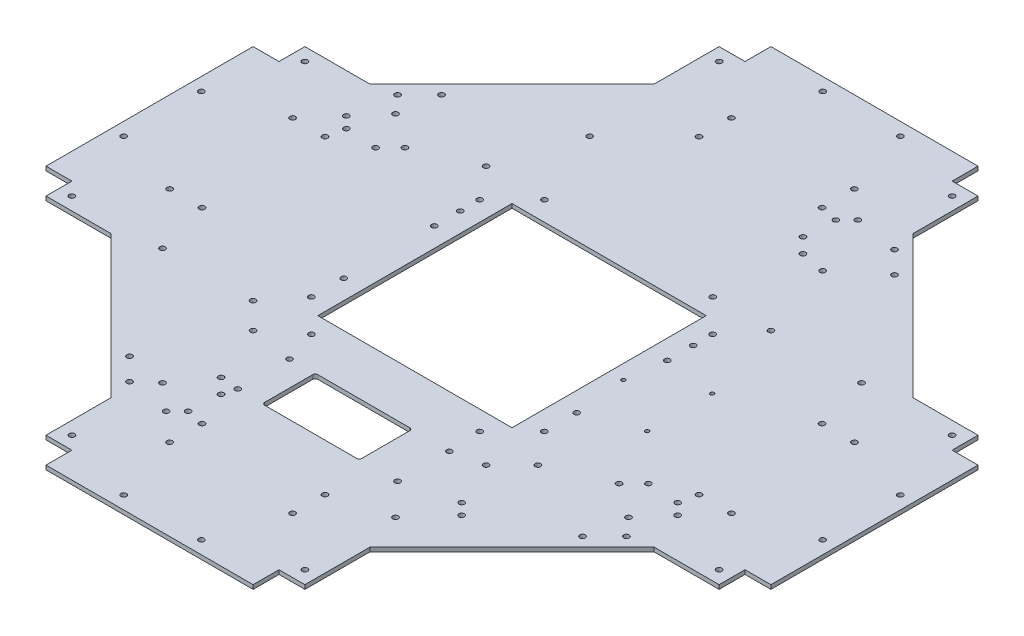
SolidWorks part; units mm, degrees
ref_plane "Front Plane" through (0, 0, 0) normal (0, 0, 1) x (1, 0, 0)
ref_plane "Top Plane" through (0, 0, 0) normal (0, 1, 0) x (1, 0, 0)
ref_plane "Right Plane" through (0, 0, 0) normal (1, 0, 0) x (0, 0, -1)
sketch "Sketch1" plane through (0, 0, 0) normal (0, 1, 0) x (1, 0, 0)
  line L0 (0, -280) -> (100, -280)
  line L1 (100, -280) -> (100, -209.6016)
  line L2 (280, -100) -> (209.6016, -100)
  line L3 (0, 0) -> (0, -280) construction
  line L4 (280, 0) -> (280, -100)
  line L5 (-280, 280) -> (280, 280) construction
  line L6 (-280, 280) -> (-280, -280) construction
  line L7 (-280, -280) -> (280, -280) construction
  line L8 (280, 280) -> (280, -280) construction
  line L9 (-280, 280) -> (280, -280) construction
  line L10 (-280, -280) -> (280, 280) construction
  line L11 (100, -209.6016) -> (209.6016, -100)
  line L12 (-280, 0) -> (-280, -100)
  line L13 (-280, -100) -> (-209.6016, -100)
  line L14 (-209.6016, -100) -> (-100, -209.6016)
  line L15 (-100, -280) -> (-100, -209.6016)
  line L16 (0, -280) -> (-100, -280)
  line L17 (0, 280) -> (-100, 280)
  line L18 (-100, 280) -> (-100, 209.6016)
  line L19 (-100, 209.6016) -> (-209.6016, 100)
  line L20 (-280, 100) -> (-209.6016, 100)
  line L21 (-280, 0) -> (-280, 100)
  line L22 (280, 0) -> (280, 100)
  line L23 (280, 100) -> (209.6016, 100)
  line L24 (209.6016, 100) -> (100, 209.6016)
  line L25 (100, 280) -> (100, 209.6016)
  line L26 (0, 280) -> (100, 280)
  line L27 (111.5258, -219.2889) -> (219.2889, -111.5258) construction
  line L28 (219.2889, -111.5258) -> (247.5732, -139.8101) construction
  line L29 (247.5732, -139.8101) -> (139.8101, -247.5732) construction
  line L30 (139.8101, -247.5732) -> (111.5258, -219.2889) construction
  line L31 (-100, -270) -> (100, -270) construction
  line L32 (-90, -280) -> (-90, 280) construction
  line L37 (-70, -70) -> (70, 70) construction
  line L38 (-70, 70) -> (70, -70) construction
  line L39 (-100, -260) -> (100, -260) construction
  line L40 (-280, 40) -> (280, 40) construction
  line L41 (0, 280) -> (0, 0) construction
  line L42 (-280, -90) -> (280, -90) construction
  line L43 (-260, -100) -> (-260, 100) construction
  line L44 (0, 0) -> (-280, 0) construction
  arc A0 (100, -280) -> (280, -100) centre (100, -100) ccw construction
  circle A1 centre (-47.5, -192) radius 2.125
  circle A2 centre (-47.5, -217) radius 2.125
  circle A3 centre (47.5, -217) radius 2.125
  circle A4 centre (47.5, -192) radius 2.125
  circle A5 centre (-192, 47.5) radius 2.125
  circle A6 centre (-217, 47.5) radius 2.125
  circle A7 centre (-192, -47.5) radius 2.125
  circle A8 centre (-217, -47.5) radius 2.125
  circle A9 centre (47.5, 192) radius 2.125
  circle A10 centre (47.5, 217) radius 2.125
  circle A11 centre (-47.5, 192) radius 2.125
  circle A12 centre (-47.5, 217) radius 2.125
  circle A13 centre (192, -47.5) radius 2.125
  circle A14 centre (217, -47.5) radius 2.125
  circle A15 centre (192, 47.5) radius 2.125
  circle A16 centre (217, 47.5) radius 2.125
  circle A17 centre (-90, -270) radius 2.125
  circle A18 centre (-30, -270) radius 2.125
  circle A19 centre (30, -270) radius 2.125
  circle A20 centre (90, -270) radius 2.125
  circle A21 centre (-270, 90) radius 2.125
  circle A22 centre (-270, 30) radius 2.125
  circle A23 centre (-270, -30) radius 2.125
  circle A24 centre (-270, -90) radius 2.125
  circle A25 centre (90, 270) radius 2.125
  circle A26 centre (30, 270) radius 2.125
  circle A27 centre (-30, 270) radius 2.125
  circle A28 centre (-90, 270) radius 2.125
  circle A29 centre (270, -90) radius 2.125
  circle A30 centre (270, -30) radius 2.125
  circle A31 centre (270, 30) radius 2.125
  circle A32 centre (270, 90) radius 2.125
  circle A33 centre (-90, -250) radius 2.125
  circle A34 centre (-90, -180) radius 2.125
  circle A35 centre (-90, -110) radius 2.125
  circle A36 centre (-90, -40) radius 2.125
  circle A37 centre (-90, 30) radius 2.125
  circle A38 centre (-90, 50) radius 2.125
  circle A39 centre (-90, 100) radius 2.125 construction
  circle A40 centre (-90, 150) radius 2.125
  circle A41 centre (-90, 200) radius 2.125 construction
  circle A42 centre (-90, 250) radius 2.125
  circle A43 centre (90, -250) radius 2.125
  circle A44 centre (90, -180) radius 2.125
  circle A45 centre (90, -110) radius 2.125
  circle A46 centre (90, -40) radius 2.125
  circle A47 centre (90, 30) radius 2.125
  circle A48 centre (90, 50) radius 2.125
  circle A49 centre (90, 100) radius 2.125 construction
  circle A50 centre (90, 150) radius 2.125
  circle A51 centre (90, 200) radius 2.125 construction
  circle A52 centre (90, 250) radius 2.125
  circle A53 centre (-250, -90) radius 2.125
  circle A54 centre (-180, -90) radius 2.125
  circle A55 centre (-110, -90) radius 2.125
  circle A56 centre (-110, 90) radius 2.125
  circle A57 centre (-180, 90) radius 2.125
  circle A58 centre (-250, 90) radius 2.125
  circle A59 centre (110, -90) radius 2.125
  circle A60 centre (180, -90) radius 2.125
  circle A61 centre (250, -90) radius 2.125
  circle A62 centre (110, 90) radius 2.125
  circle A63 centre (180, 90) radius 2.125
  circle A64 centre (250, 90) radius 2.125
  point P33 (0, 0)
  point P68 (0, 0)
  point P107 (0, 0)
  dimension "D10" = 25
  dimension "4.25" = 4.25
  dimension "D11" = 4.25
  dimension "D16" = 4.25
  dimension "D24" = 4.25
  dimension "D28" = 4.25
  dimension "D32" = 4.25
  dimension "D1" = 560
  dimension "D2" = 90
  dimension "D3" = 280
  dimension "D4" = 4
  dimension "D5" = 100
  dimension "D6" = 155
  dimension "D7" = 152.4
  dimension "D8" = 15
  dimension "D9" = 40
  dimension "D12" = 47.5
  dimension "D13" = 63
  dimension "D15" = 10
  dimension "D17" = 10
  dimension "D18" = 76.2
  dimension "D23" = 10
  dimension "D25" = 10
  dimension "D26" = 300
  dimension "D29" = 10
  dimension "D31" = 20
  dimension "D33" = 10
  dimension "D21" = 4
  dimension "D27" = 5
  dimension "D30" = 5
  dimension "D34" = 3
  dimension "D14" = 4
  dimension "D22" = 4
extrude "Boss-Extrude1" add sketch "Sketch1" along normal blind 3.175 contours L26 L17 L18 L19 L20 L21 L12 L13 L14 L15 L16 L0 L1 L11 L2 L4 L22 L23 L24 L25
sketch "Sketch2" plane through (0, 3.175, 0) normal (0, 1, 0) x (1, 0, 0)
  line L0 (-90, -280) -> (-90, 280) construction
  line L1 (-75, -75) -> (75, -75)
  line L2 (-75, -75) -> (-75, 75)
  line L3 (-75, 75) -> (75, 75)
  line L4 (75, -75) -> (75, 75)
  line L5 (-75, -75) -> (75, 75) construction
  line L6 (-75, 75) -> (75, -75) construction
  line L7 (-90, -280) -> (-90, 280) construction
  line L8 (-75, 0) -> (75, 0) construction
  line L9 (0, 75) -> (0, -75) construction
  line L10 (-110, 90) -> (110, 90) construction
  line L11 (37.5, -135) -> (-37.5, -135) construction
  line L16 (-37.5, -155.5) -> (37.5, -155.5)
  line L17 (-37.5, -155.5) -> (-37.5, -114.5)
  line L18 (-37.5, -114.5) -> (37.5, -114.5)
  line L19 (37.5, -155.5) -> (37.5, -114.5)
  line L20 (-37.5, -155.5) -> (37.5, -114.5) construction
  line L21 (-37.5, -114.5) -> (37.5, -155.5) construction
  line L22 (128.2843, -167.1751) -> (98.0356, -136.9265) construction
  line L23 (146.0396, -78.7091) -> (184.862, -39.8867) construction
  line L24 (92.9289, -202.5305) -> (202.5305, -92.9289)
  line L25 (92.9289, -202.5305) -> (202.5305, -92.9289) construction
  line L26 (170.0036, -125.4558) -> (137.8448, -93.2971) construction
  circle A0 centre (66.6, -115) radius 2.125
  circle A1 centre (-90, 65) radius 2.125
  circle A2 centre (-90, -65) radius 2.125
  circle A3 centre (90, -65) radius 2.125
  circle A4 centre (90, 65) radius 2.125
  circle A5 centre (-65, 90) radius 2.125
  circle A6 centre (65, 90) radius 2.125
  circle A7 centre (65, -90) radius 2.125
  circle A8 centre (-65, -90) radius 2.125
  circle A9 centre (66.6, -155) radius 2.125
  circle A10 centre (-56.9, -115) radius 2.1
  circle A11 centre (-56.9, -155) radius 2.1
  circle A12 centre (174.9533, -120.5061) radius 2.125
  circle A13 centre (191.9239, -103.5355) radius 2.125
  circle A14 centre (153.737, -71.0118) radius 2.125
  circle A15 centre (165.0507, -59.6981) radius 2.125
  circle A16 centre (-120.5061, -174.9533) radius 2.125
  circle A17 centre (-103.5355, -191.9239) radius 2.125
  circle A18 centre (-71.0118, -153.737) radius 2.125
  circle A19 centre (-59.6981, -165.0507) radius 2.125
  circle A20 centre (-174.9533, 120.5061) radius 2.125
  circle A21 centre (-191.9239, 103.5355) radius 2.125
  circle A22 centre (-153.737, 71.0118) radius 2.125
  circle A23 centre (-165.0507, 59.6981) radius 2.125
  circle A24 centre (120.5061, 174.9533) radius 2.125
  circle A25 centre (103.5355, 191.9239) radius 2.125
  circle A26 centre (71.0118, 153.737) radius 2.125
  circle A27 centre (59.6981, 165.0507) radius 2.125
  circle A28 centre (114.1421, -153.033) radius 2.125
  circle A29 centre (105.6569, -144.5477) radius 2.1
  circle A30 centre (197.5807, -69.5944) radius 2.125
  circle A31 centre (189.0955, -61.1091) radius 2.1
  circle A32 centre (-61.1091, -189.0955) radius 2.1
  circle A33 centre (-69.5944, -197.5807) radius 2.125
  circle A34 centre (-189.0955, 61.1091) radius 2.1
  circle A35 centre (-197.5807, 69.5944) radius 2.125
  circle A36 centre (61.1091, 189.0955) radius 2.1
  circle A37 centre (69.5944, 197.5807) radius 2.125
  point P0 (0, 0)
  point P6 (0, -135)
  point P86 (0, 0)
  point P111 (0, 0)
  dimension "D3" = 4.25
  dimension "D5" = 4.25
  dimension "D11" = 4.25
  dimension "D14" = 4.2
  dimension "D18" = 4.25
  dimension "D20" = 4.25
  dimension "D23" = 4.25
  dimension "D25" = 4.25
  dimension "D29" = 4.25
  dimension "D31" = 4.2
  dimension "D1" = 150
  dimension "D2" = 150
  dimension "D4" = 10
  dimension "D6" = 10
  dimension "D7" = 75
  dimension "D8" = 41
  dimension "D9" = 0
  dimension "D10" = 135
  dimension "D12" = 20
  dimension "D13" = 66.6
  dimension "D15" = 19.4
  dimension "D16" = 20
  dimension "D19" = 116
  dimension "D21" = 24
  dimension "D22" = 50
  dimension "D24" = 53.85
  dimension "D26" = 16
  dimension "D28" = 50
  dimension "D30" = 20
  dimension "D32" = 12
  dimension "D33" = 59
  dimension "D17" = 10
  dimension "D27" = 4
  dimension "D34" = 4
extrude "Cut-Extrude1" cut sketch "Sketch2" against normal through all
fillet "Fillet1" radius 2 4 edges at (-37.5, 1.5875, 155.5) (37.5, 1.5875, 155.5) (37.5, 1.5875, 114.5) (-37.5, 1.5875, 114.5)
sketch "Sketch3" plane through (0, 3.175, 0) normal (0, 1, 0) x (1, 0, 0)
  line L0 (-260, 80) -> (-280, 80)
  line L1 (80, -260) -> (100, -260)
  line L2 (80, -260) -> (80, -280)
  line L3 (80, -280) -> (100, -280)
  line L4 (100, -260) -> (100, -280)
  line L5 (80, -260) -> (100, -280) construction
  line L6 (80, -280) -> (100, -260) construction
  line L7 (-80, -260) -> (-100, -260)
  line L8 (-80, -260) -> (-80, -280)
  line L9 (-80, -280) -> (-100, -280)
  line L10 (-100, -260) -> (-100, -280)
  line L11 (-80, -260) -> (-100, -280) construction
  line L12 (-80, -280) -> (-100, -260) construction
  line L13 (-260, 80) -> (-260, 100)
  line L14 (-260, 100) -> (-280, 100)
  line L15 (-280, 80) -> (-280, 100)
  line L16 (-260, -80) -> (-280, -80)
  line L17 (-260, -80) -> (-260, -100)
  line L18 (-260, -100) -> (-280, -100)
  line L19 (-280, -80) -> (-280, -100)
  line L20 (80, 260) -> (80, 280)
  line L21 (80, 260) -> (100, 260)
  line L22 (100, 260) -> (100, 280)
  line L23 (80, 280) -> (100, 280)
  line L24 (-80, 260) -> (-80, 280)
  line L25 (-80, 260) -> (-100, 260)
  line L26 (-100, 260) -> (-100, 280)
  line L27 (-80, 280) -> (-100, 280)
  line L28 (260, -80) -> (280, -80)
  line L29 (260, -80) -> (260, -100)
  line L30 (260, -100) -> (280, -100)
  line L31 (280, -80) -> (280, -100)
  line L32 (260, 80) -> (280, 80)
  line L33 (260, 80) -> (260, 100)
  line L34 (260, 100) -> (280, 100)
  line L35 (280, 80) -> (280, 100)
  point P0 (90, -270)
  point P7 (-90, -270)
  point P41 (0, 0)
extrude "Cut-Extrude2" cut sketch "Sketch3" against normal through all
sketch "Sketch4" plane through (0, 3.175, 0) normal (0, 1, 0) x (1, 0, 0)
  line L0 (86, 0) -> (115.5449, 0) construction
  circle A0 centre (115, 0) radius 29 construction
  circle A1 centre (129.5, -25.1147) radius 1.5
  circle A2 centre (86, 0) radius 1.5
  circle A3 centre (129.5, 25.1147) radius 1.5
  point P11 (0, 0)
  point P12 (0, 0)
  point P13 (0, 0)
  dimension "D1" = 58
  dimension "D2" = 3
  dimension "D3" = 3
extrude "Cut-Extrude3" cut sketch "Sketch4" against normal up to next
